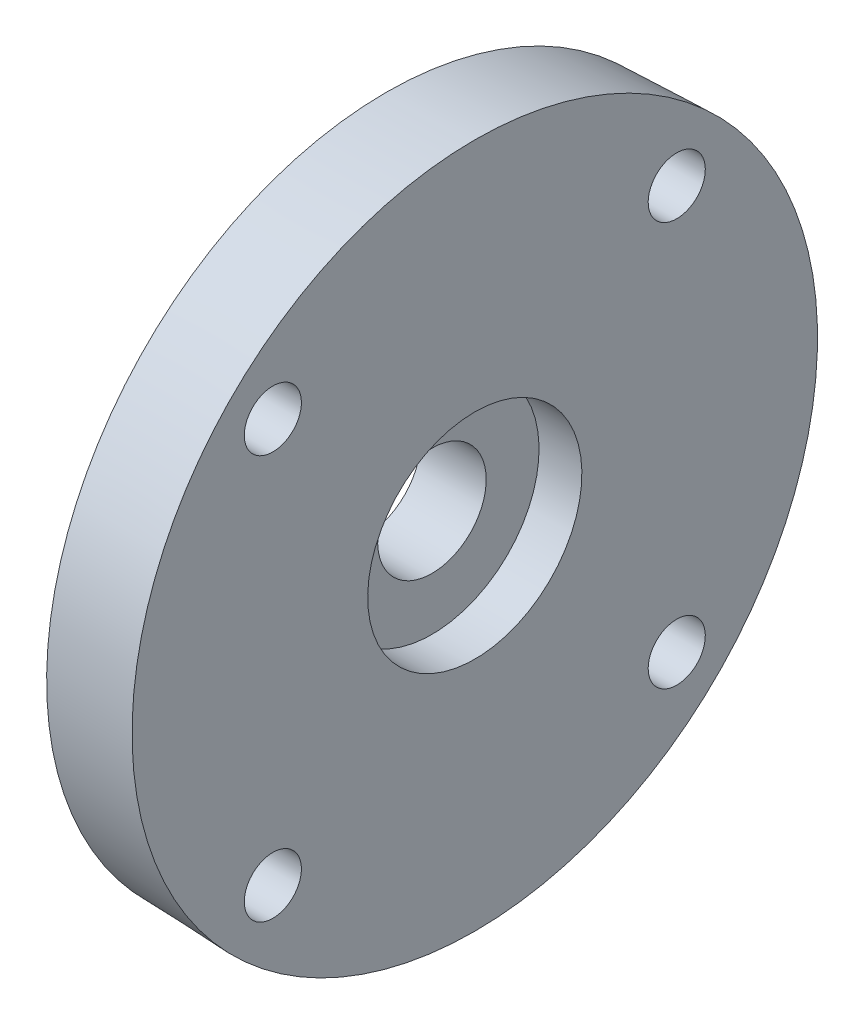
SolidWorks part; units mm, degrees
material "Delrin 2700 NC010, Low Viscosity Acetal Copolymer (SS)"
ref_plane "Front Plane" through (0, 0, 0) normal (0, 0, 1) x (1, 0, 0)
ref_plane "Top Plane" through (0, 0, 0) normal (0, 1, 0) x (1, 0, 0)
ref_plane "Right Plane" through (0, 0, 0) normal (1, 0, 0) x (0, 0, -1)
sketch "Sketch1" plane through (0, 0, 0) normal (0, 0, 1) x (1, 0, 0)
  line L0 (0, 0) -> (-7.874, 0) construction
  line L1 (-7.874, 8.255) -> (-7.874, 30.205)
  line L2 (-7.874, 30.205) -> (0, 30.48)
  line L3 (0, 30.48) -> (0, 4.826)
  line L4 (0, 4.826) -> (-9.652, 4.826)
  line L5 (-7.874, 8.255) -> (-9.652, 8.255)
  line L6 (-9.652, 8.255) -> (-9.652, 4.826)
  point P3 (-7.874, 12.827)
  point P8 (-9.2316, 3.9878)
  point P11 (-7.874, 11.5238)
  dimension "D1" = 9.652
  dimension "D2" = 7.874
  dimension "D3" = 9.652
  dimension "D4" = 16.51
  dimension "D5" = 60.96
  dimension "D6" = 2
revolve "Revolve1" add sketch "Sketch1" angle 360 about L0
sketch "Sketch2" plane through (-7.874, 0, 0) normal (-1, 0, 0) x (0, 0, 1)
  line L0 (-17.9605, 17.9605) -> (17.9605, -17.9605) construction
  line L1 (17.9605, 17.9605) -> (-17.9605, -17.9605) construction
  circle A0 centre (-17.9605, 17.9605) radius 2.54
  circle A1 centre (17.9605, 17.9605) radius 2.54
  circle A2 centre (17.9605, -17.9605) radius 2.54
  circle A3 centre (-17.9605, -17.9605) radius 2.54
  dimension "D1" = 5.08
  dimension "D2" = 50.8
extrude "Cut-Extrude1" cut sketch "Sketch2" against normal through all
sketch "Sketch3" plane through (0, 0, 0) normal (1, 0, 0) x (0, 0, -1)
  circle A0 centre (0, 0) radius 9.525
  dimension "D1" = 19.05
extrude "Cut-Extrude2" cut sketch "Sketch3" against normal blind 3.81
